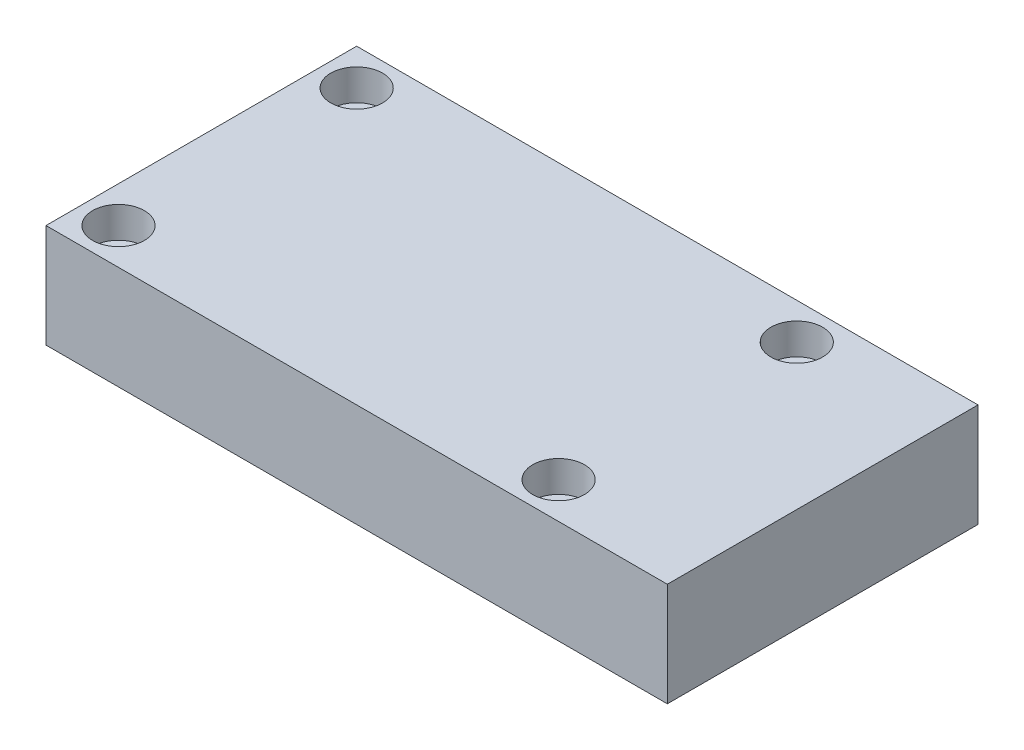
SolidWorks part; units mm, degrees
ref_plane "Front Plane" through (0, 0, 0) normal (0, 0, 1) x (1, 0, 0)
ref_plane "Top Plane" through (0, 0, 0) normal (0, 1, 0) x (1, 0, 0)
ref_plane "Right Plane" through (0, 0, 0) normal (1, 0, 0) x (0, 0, -1)
sketch "Sketch1" plane through (0, 0, 0) normal (0, 1, 0) x (1, 0, 0)
  line L1 (-55.7302, -42.3668) -> (96.6698, -42.3668)
  line L2 (-55.7302, -42.3668) -> (-55.7302, 33.8332)
  line L3 (-55.7302, 33.8332) -> (96.6698, 33.8332)
  line L4 (96.6698, -42.3668) -> (96.6698, 33.8332)
  dimension "D1" = 76.2
  dimension "D2" = 152.4
extrude "Boss-Extrude1" add sketch "Sketch1" along normal blind 25.4
sketch "Sketch2" plane through (0, 25.4, 0) normal (0, 1, 0) x (1, 0, 0)
  line L0 (-55.7302, -42.3668) -> (96.6698, -42.3668) construction
  line L3 (-55.7302, 33.8332) -> (-55.7302, -42.3668) construction
  circle A0 centre (-46.8402, 24.9432) radius 6.35
  circle A1 centre (-46.8402, -33.4768) radius 6.35
  circle A2 centre (61.1098, 24.9432) radius 6.35
  circle A3 centre (61.1098, -33.4768) radius 6.35
  dimension "D1" = 12.7
  dimension "D2" = 12.7
  dimension "D3" = 12.7
  dimension "D4" = 12.7
  dimension "D5" = 107.95
  dimension "D6" = 58.42
  dimension "D7" = 8.89
  dimension "D8" = 8.89
extrude "Cut-Extrude1" cut sketch "Sketch2" against normal blind 7.62
